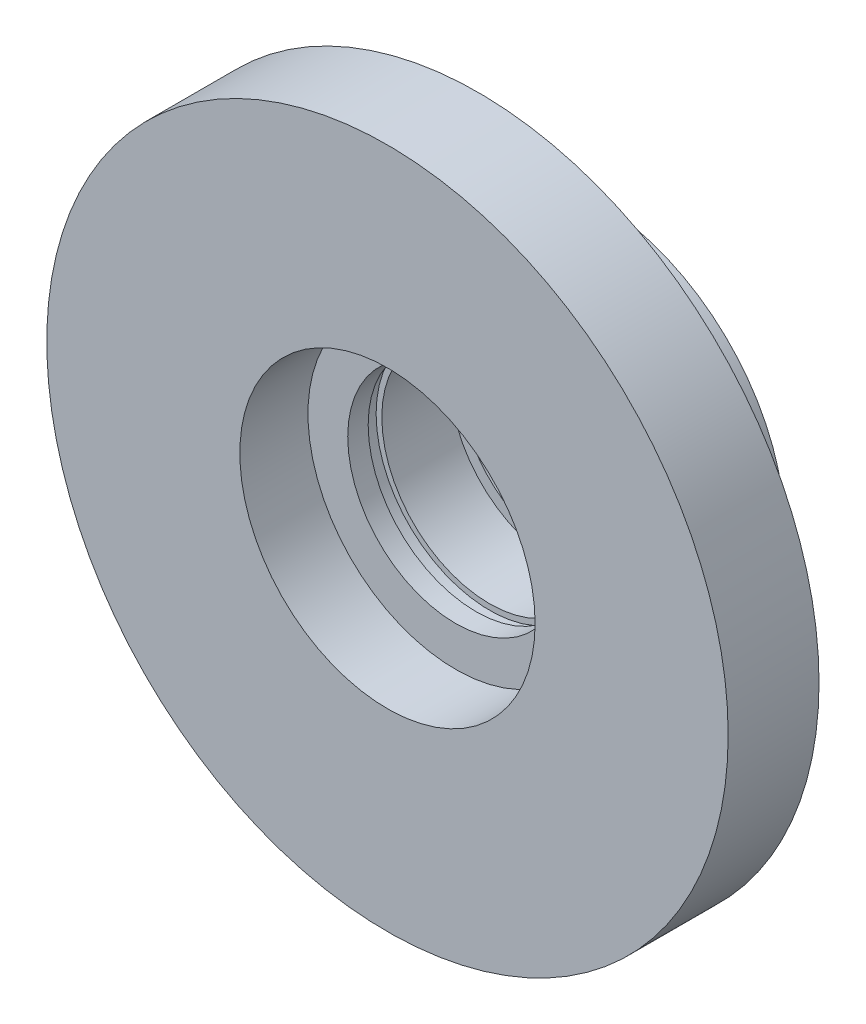
SolidWorks part; units mm, degrees
ref_plane "Front Plane" through (0, 0, 0) normal (0, 0, 1) x (1, 0, 0)
ref_plane "Top Plane" through (0, 0, 0) normal (0, 1, 0) x (1, 0, 0)
ref_plane "Right Plane" through (0, 0, 0) normal (1, 0, 0) x (0, 0, -1)
sketch "Sketch1" plane through (0, 0, 0) normal (0, 0, 1) x (1, 0, 0)
  circle A0 centre (0, 0) radius 17
  circle A1 centre (0, 0) radius 13
  dimension "D1" = 4
  dimension "D2" = 34
extrude "Boss-Extrude1" add sketch "Sketch1" along normal blind 10
sketch "Sketch2" plane through (0, 0, 10) normal (0, 0, 1) x (1, 0, 0)
  circle A0 centre (0, 0) radius 30
  circle A1 centre (0, 0) radius 13 construction
  circle A2 centre (0, 0) radius 13
  dimension "D1" = 60
extrude "Boss-Extrude2" add sketch "Sketch2" along normal blind 8
hole_wizard "Ø4.2 (4.2) Diameter Hole1" [suppressed] positions "Sketch3" profile "Sketch4" hole size "Ø4.2" standard "DIN"
sketch "Sketch3" plane through (0, 0, 18) normal (0, 0, 1) x (1, 0, 0)
  line L1 (0, 17) -> (0, 30) construction
  circle A2 centre (0, 0) radius 17 construction
  circle A3 centre (0, 0) radius 17 construction
  circle A4 centre (0, 0) radius 30 construction
  point P22 (0, 23.5)
  point P28 (20.3516, 11.75)
  point P29 (20.3516, -11.75)
  point P30 (0, -23.5)
  point P31 (-20.3516, -11.75)
  point P32 (-20.3516, 11.75)
  dimension "D1" = 6
sketch "Sketch4" plane through (-20.3516, 11.75, 18) normal (1, 0, 0) x (0, -1, 0)
  line L0 (0, 0) -> (0, 26.2618)
  line L1 (0, 26.2618) -> (2.1, 25)
  line L2 (2.1, 25) -> (2.1, 0)
  line L5 (2.1, 0) -> (0, 0)
  line L10 (0, 26.2618) -> (-2.1, 25) construction
  line L11 (0, -6.35) -> (0, 107.95) construction
  dimension "Hole Dia." = 4.2
  dimension "Hole Depth" = 25
  dimension "Drill Angle" = 118
sketch "Sketch5" [suppressed] plane through (0, 0, 18) normal (0, 0, 1) x (1, 0, 0)
  circle A0 centre (0, 0) radius 17 construction
  circle A1 centre (0, 0) radius 17 construction
  circle A2 centre (-20.3516, 11.75) radius 6.5
  circle A3 centre (0, 23.5) radius 6.5
  circle A4 centre (20.3516, 11.75) radius 6.5
  circle A5 centre (20.3516, -11.75) radius 6.5
  circle A6 centre (0, -23.5) radius 6.5
  circle A7 centre (-20.3516, -11.75) radius 6.5
  circle A8 centre (0, 0) radius 30 construction
  circle A9 centre (0, 0) radius 30
  circle A10 centre (0, 0) radius 18
  circle M11 centre (0, 0) radius 30
  dimension "D1" = 1
extrude "Cut-Extrude1" [suppressed] cut sketch "Sketch5" against normal through all contours A7 A1 A2 M11 | A3 A2 A1 M11 | A4 A3 A1 M11 | A5 A4 A1 M11 | A6 A5 A1 M11 | A7 A6 A1 M11
fillet "Fillet1" [suppressed] radius 6
sketch "Sketch6" plane through (0, 0, 0) normal (0, 0, -1) x (-1, 0, 0)
  circle A0 centre (0, 0) radius 8.5
  circle A1 centre (0, 0) radius 17 construction
  circle A2 centre (0, 0) radius 17
  dimension "D1" = 17
extrude "Boss-Extrude3" add sketch "Sketch6" against normal blind 3
sketch "Sketch7" plane through (0, 0, 3) normal (0, 0, 1) x (1, 0, 0)
  circle A0 centre (0, 0) radius 9.5
  circle A2 centre (0, 0) radius 13 construction
  circle A3 centre (0, 0) radius 13
  dimension "D1" = 19
extrude "Boss-Extrude4" add sketch "Sketch7" along normal blind 9
sketch "Sketch8" plane through (0, 0, 12) normal (0, 0, 1) x (1, 0, 0)
  circle A0 centre (0, 0) radius 10
  dimension "D1" = 20
extrude "Cut-Extrude2" cut sketch "Sketch8" against normal blind 1.2 from offset 1.8 offset against normal yes
